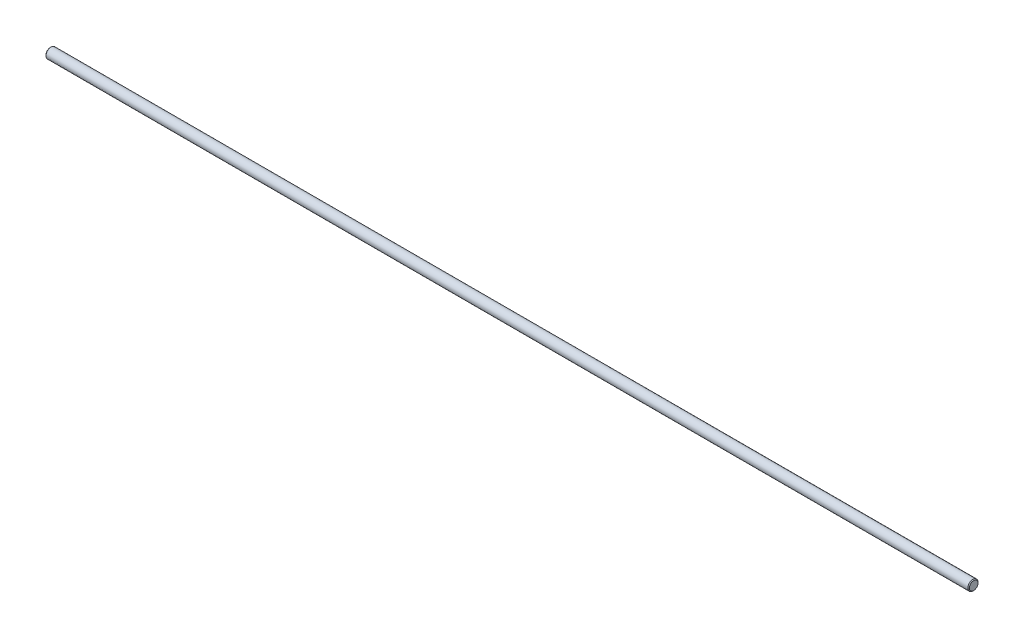
SolidWorks part; units mm, degrees
material "Galvanized Steel"
ref_plane "Front Plane" through (0, 0, 0) normal (0, 0, 1) x (1, 0, 0)
ref_plane "Top Plane" through (0, 0, 0) normal (0, 1, 0) x (1, 0, 0)
ref_plane "Right Plane" through (0, 0, 0) normal (1, 0, 0) x (0, 0, -1)
sketch "Sketch1" plane through (0, 0, 0) normal (1, 0, 0) x (0, 0, -1)
  circle A0 centre (0, 0) radius 2
  dimension "D1" = 4
extrude "Boss-Extrude1" add sketch "Sketch1" along normal mid plane 364
chamfer "Chamfer1" distance 0.3 angle 45 2 edges at (-182, 0, -2) (182, 0, -2)
